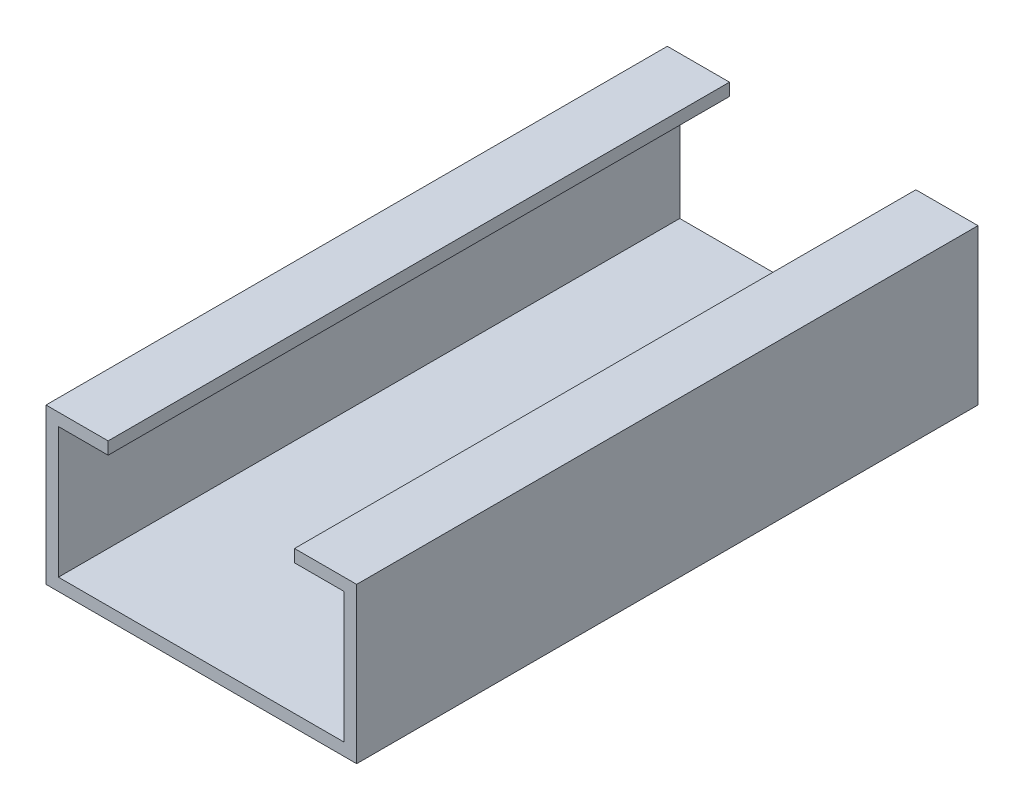
SolidWorks part; units mm, degrees
ref_plane "Front Plane" through (0, 0, 0) normal (0, 0, 1) x (1, 0, 0)
ref_plane "Top Plane" through (0, 0, 0) normal (0, 1, 0) x (1, 0, 0)
ref_plane "Right Plane" through (0, 0, 0) normal (1, 0, 0) x (0, 0, -1)
sketch "Sketch1" plane through (0, 0, 0) normal (0, 0, 1) x (1, 0, 0)
  line L0 (-46, 21) -> (46, 21) construction
  line L1 (-50, 25) -> (50, 25) construction
  line L2 (-50, 25) -> (-50, -25) construction
  line L3 (-50, -25) -> (50, -25) construction
  line L4 (50, 25) -> (50, -25) construction
  line L5 (-50, 25) -> (50, -25) construction
  line L6 (-50, -25) -> (50, 25) construction
  line L7 (46, 21) -> (46, -21) construction
  line L8 (-46, -21) -> (46, -21) construction
  line L9 (-46, 21) -> (-46, -21) construction
  line L10 (-30, 25) -> (-50, 25)
  line L11 (-50, 25) -> (-50, -25)
  line L12 (-50, -25) -> (50, -25)
  line L13 (50, -25) -> (50, 25)
  line L14 (50, 25) -> (30, 25)
  line L15 (30, 25) -> (30, 21)
  line L16 (30, 21) -> (46, 21)
  line L17 (46, 21) -> (46, -21)
  line L18 (46, -21) -> (-46, -21)
  line L19 (-46, -21) -> (-46, 21)
  line L20 (-46, 21) -> (-30, 21)
  line L21 (-30, 21) -> (-30, 25)
  point P0 (0, 0)
  dimension "D1" = 50
  dimension "D2" = 100
  dimension "D4" = 20
  dimension "D3" = 4
extrude "Boss-Extrude1" add sketch "Sketch1" along normal blind 200
